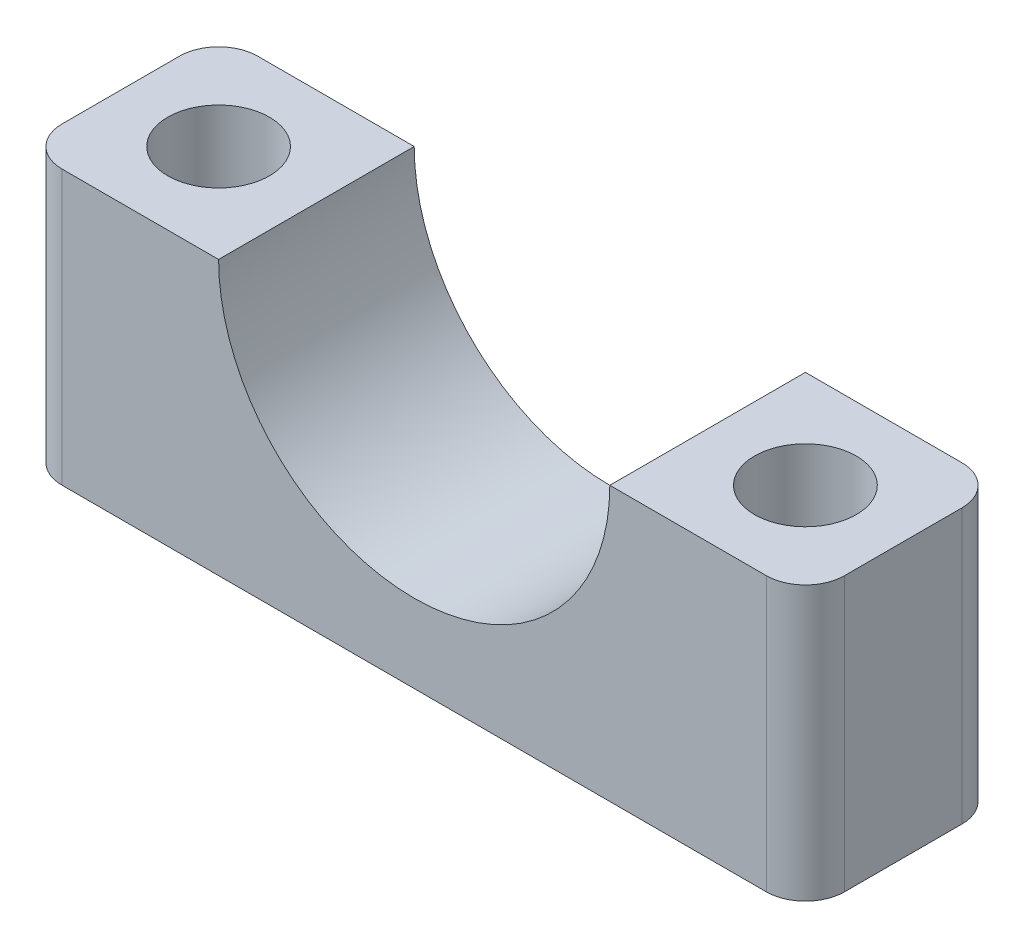
SolidWorks part; units mm, degrees
ref_plane "Front Plane" through (0, 0, 0) normal (0, 0, 1) x (1, 0, 0)
ref_plane "Top Plane" through (0, 0, 0) normal (0, 1, 0) x (1, 0, 0)
ref_plane "Right Plane" through (0, 0, 0) normal (1, 0, 0) x (0, 0, -1)
sketch "Sketch1" plane through (0, 0, 0) normal (0, 0, 1) x (1, 0, 0)
  line L0 (10, 0) -> (20, 0)
  line L1 (20, 0) -> (20, -14)
  line L5 (-20, 0) -> (-10, 0)
  line L6 (-20, 0) -> (-20, -14)
  line L7 (-20, -14) -> (20, -14)
  arc A0 (-10, 0) -> (10, 0) centre (0, 0) ccw
  dimension "D3" = 20
  dimension "D2" = 40
  dimension "D4" = 14
extrude "Boss-Extrude1" add sketch "Sketch1" along normal blind 10
fillet "Fillet1" radius 2 4 edges at (-20, -7, 0) (-20, -7, 10) (20, -7, 0) (20, -7, 10)
sketch "Sketch4" plane through (0, 0, 0) normal (0, 1, 0) x (1, 0, 0)
  line L0 (-15, -5) -> (15, -5) construction
  line L1 (0, 0) -> (0, -5) construction
  circle A0 centre (-15, -5) radius 2.6
  circle A1 centre (15, -5) radius 2.6
  point P7 (0, -5)
  dimension "D2" = 5.2
  dimension "D1" = 30
  dimension "D3" = 5
extrude "Cut-Extrude2" cut sketch "Sketch4" against normal through all
